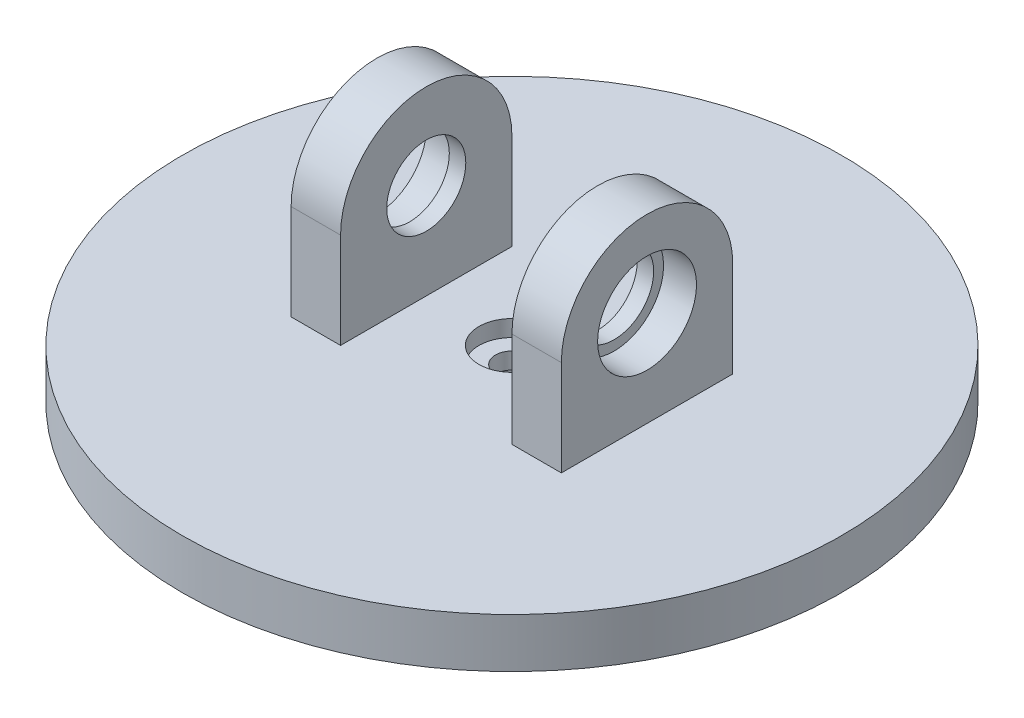
SolidWorks part; units mm, degrees
ref_plane "Ebene vorne" through (0, 0, 0) normal (0, 0, 1) x (1, 0, 0)
ref_plane "Ebene oben" through (0, 0, 0) normal (0, 1, 0) x (1, 0, 0)
ref_plane "Ebene rechts" through (0, 0, 0) normal (1, 0, 0) x (0, 0, -1)
sketch "Skizze1" plane through (0, 0, 0) normal (0, 1, 0) x (1, 0, 0)
  circle A0 centre (0, 0) radius 100
extrude "Aufsatz-Linear austragen1" add sketch "Skizze1" along normal blind 15 contours A0
sketch "Skizze2" plane through (0, 15, 0) normal (0, 1, 0) x (1, 0, 0)
  line L0 (-26, 25) -> (-26, 26)
  line L1 (-41, -26) -> (41, -26)
  line L2 (-41, -26) -> (-41, 26)
  line L3 (-41, 26) -> (41, 26)
  line L4 (41, -26) -> (41, 26)
  line L5 (-41, -26) -> (41, 26) construction
  line L6 (-41, 26) -> (41, -26) construction
  line L7 (-26, -25) -> (26, -25)
  line L8 (-26, -25) -> (-26, 25)
  line L9 (-26, 25) -> (26, 25)
  line L10 (26, -25) -> (26, 25)
  line L11 (-26, -25) -> (26, 25) construction
  line L12 (-26, 25) -> (26, -25) construction
  line L13 (-26, 26) -> (-26, -26)
  line L14 (-26, -26) -> (26, -26)
  line L15 (26, -26) -> (26, 26)
  point P0 (0, 0)
  point P6 (0, 0)
  dimension "D1" = 52
  dimension "D2" = 50
  dimension "D3" = 15
  dimension "D4" = 1
extrude "Aufsatz-Linear austragen2" add sketch "Skizze2" along normal blind 55 contours L13 L8 L0 L3 L2 L1 | L15 L1 L4 L3 L10
sketch "Skizze3" plane through (-41, 0, 0) normal (-1, 0, 0) x (0, 0, 1)
  line L0 (-26, 44) -> (-26, 70)
  line L1 (-26, 70) -> (26, 70)
  line L2 (26, 70) -> (26, 44)
  circle A0 centre (0, 44) radius 26
  circle A1 centre (0, 44) radius 10
  line M4 (26, 15) -> (26, 70)
  line M5 (26, 70) -> (-26, 70)
  line M6 (-26, 70) -> (-26, 15)
extrude "Schnitt-Linear austragen5" cut sketch "Skizze3" against normal up to surface (82 mm away) contours A0 L1 M6 | A0 M4 M5 up to face at (41, 42.5, 0)
sketch "Skizze7" plane through (-41, 0, 0) normal (-1, 0, 0) x (0, 0, 1)
  circle A0 centre (0, 44) radius 15
extrude "Schnitt-Linear austragen6" cut sketch "Skizze7" against normal blind 10
sketch "Skizze8" plane through (-26, 0, 0) normal (1, 0, 0) x (0, 0, -1)
  circle A0 centre (0, 44) radius 10
sketch "Skizze10" plane through (0, 15, 0) normal (0, 1, 0) x (1, 0, 0)
  circle A0 centre (0, 0) radius 10
extrude "Schnitt-Linear austragen9" cut sketch "Skizze10" against normal blind 5
sketch "Skizze11" plane through (0, 0, 0) normal (0, -1, 0) x (1, 0, 0)
  circle A0 centre (0, 0) radius 10
extrude "Schnitt-Linear austragen10" cut sketch "Skizze11" against normal blind 5
sketch "Skizze12" plane through (0, 0, 0) normal (0, -1, 0) x (1, 0, 0)
  circle A0 centre (0, 0) radius 90
  circle A1 centre (0, 0) radius 84
extrude "Schnitt-Linear austragen11" cut sketch "Skizze12" against normal blind 2.8
sketch "Skizze13" plane through (0, 5, 0) normal (0, -1, 0) x (1, 0, 0)
  circle A0 centre (0, 0) radius 5
extrude "Schnitt-Linear austragen12" cut sketch "Skizze13" against normal blind 5
sketch "Skizze14" plane through (-26, 0, 0) normal (1, 0, 0) x (0, 0, -1)
  circle A0 centre (0, 44) radius 12
extrude "Schnitt-Linear austragen13" cut sketch "Skizze14" against normal blind 10 contours A0
mirror "Spiegeln1" about plane through (0, 0, 0) normal (1, 0, 0) of "Schnitt-Linear austragen6", "Schnitt-Linear austragen13"
